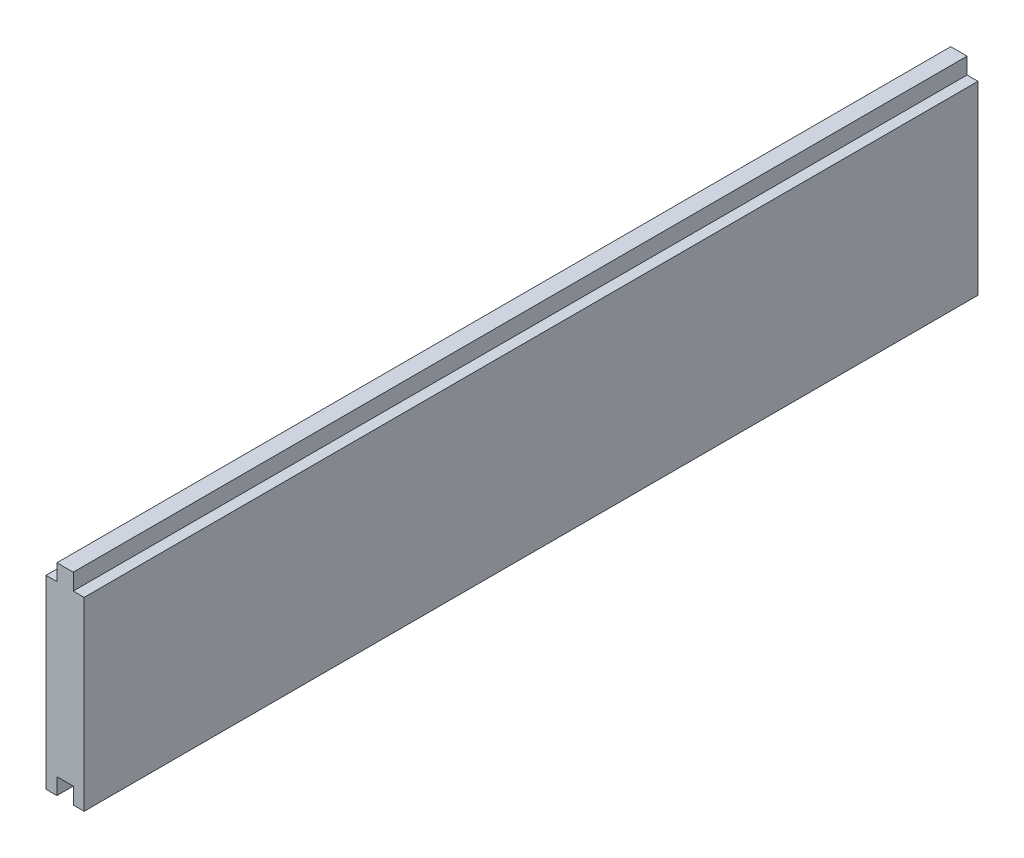
SolidWorks part; units mm, degrees
material "Сосна"
ref_plane "Спереди" through (0, 0, 0) normal (0, 0, 1) x (1, 0, 0)
ref_plane "Сверху" through (0, 0, 0) normal (0, 1, 0) x (1, 0, 0)
ref_plane "Справа" through (0, 0, 0) normal (1, 0, 0) x (0, 0, -1)
sketch "Эскиз1" plane through (0, 0, 0) normal (0, 0, 1) x (1, 0, 0)
  line L0 (0, 0) -> (0, 170)
  line L1 (35, 170) -> (25, 170)
  line L2 (35, 170) -> (35, 0)
  line L3 (35, 0) -> (25, 0)
  line L4 (25, 0) -> (25, 15)
  line L5 (25, 15) -> (10, 15)
  line L6 (10, 15) -> (10, 0)
  line L7 (10, 0) -> (0, 0)
  line L8 (25, 170) -> (25, 185)
  line L9 (25, 185) -> (10, 185)
  line L10 (10, 185) -> (10, 170)
  line L11 (10, 170) -> (0, 170)
  dimension "D1" = 170
  dimension "D2" = 35
  dimension "D3" = 10
  dimension "D4" = 15
extrude "Бобышка-Вытянуть1" add sketch "Эскиз1" against normal blind 820
